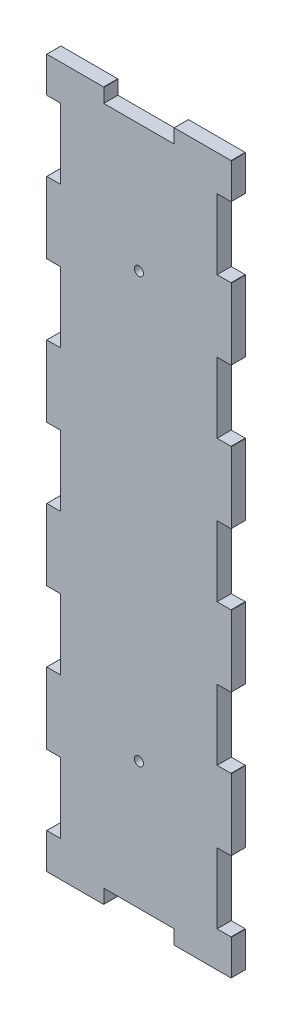
SolidWorks part; units mm, degrees
ref_plane "Front Plane" through (0, 0, 0) normal (0, 0, 1) x (1, 0, 0)
ref_plane "Top Plane" through (0, 0, 0) normal (0, 1, 0) x (1, 0, 0)
ref_plane "Right Plane" through (0, 0, 0) normal (1, 0, 0) x (0, 0, -1)
sketch "Model" plane through (0, 0, 0) normal (0, 0, 1) x (1, 0, 0)
  line L0 (-12.44, -124.95) -> (-12.43, -124.94)
  line L1 (-12.43, -124.94) -> (-12.42, -124.92)
  line L2 (-12.42, -124.92) -> (-12.41, -124.91)
  line L3 (-12.41, -124.91) -> (-12.4, -124.89)
  line L4 (-12.4, -124.89) -> (-12.4, -119.97)
  line L5 (-12.4, -119.97) -> (12.4, -119.97)
  line L6 (12.4, -119.97) -> (12.4, -124.89)
  line L7 (12.4, -124.89) -> (12.42, -124.93)
  line L8 (12.42, -124.93) -> (12.43, -124.94)
  line L9 (12.43, -124.94) -> (12.45, -124.95)
  line L10 (12.45, -124.95) -> (12.46, -124.96)
  line L11 (12.46, -124.96) -> (12.48, -124.97)
  line L12 (12.48, -124.97) -> (32.52, -124.97)
  line L13 (32.52, -124.97) -> (32.56, -124.95)
  line L14 (32.56, -124.95) -> (32.57, -124.94)
  line L15 (32.57, -124.94) -> (32.58, -124.92)
  line L16 (32.58, -124.92) -> (32.59, -124.91)
  line L17 (32.59, -124.91) -> (32.6, -124.89)
  line L18 (32.6, -124.89) -> (32.6, -112.48)
  line L19 (32.6, -112.48) -> (32.58, -112.44)
  line L20 (32.58, -112.44) -> (32.57, -112.43)
  line L21 (32.57, -112.43) -> (32.55, -112.42)
  line L22 (32.55, -112.42) -> (32.54, -112.41)
  line L23 (32.54, -112.41) -> (32.52, -112.4)
  line L24 (32.52, -112.4) -> (27.6, -112.4)
  line L25 (27.6, -112.4) -> (27.6, -87.6)
  line L26 (27.6, -87.6) -> (32.52, -87.6)
  line L27 (32.52, -87.6) -> (32.56, -87.58)
  line L28 (32.56, -87.58) -> (32.57, -87.57)
  line L29 (32.57, -87.57) -> (32.58, -87.55)
  line L30 (32.58, -87.55) -> (32.59, -87.54)
  line L31 (32.59, -87.54) -> (32.6, -87.52)
  line L32 (32.6, -87.52) -> (32.6, -62.48)
  line L33 (32.6, -62.48) -> (32.58, -62.44)
  line L34 (32.58, -62.44) -> (32.57, -62.43)
  line L35 (32.57, -62.43) -> (32.55, -62.42)
  line L36 (32.55, -62.42) -> (32.54, -62.41)
  line L37 (32.54, -62.41) -> (32.52, -62.4)
  line L38 (32.52, -62.4) -> (27.6, -62.4)
  line L39 (27.6, -62.4) -> (27.6, -37.6)
  line L40 (27.6, -37.6) -> (32.52, -37.6)
  line L41 (32.52, -37.6) -> (32.56, -37.58)
  line L42 (32.56, -37.58) -> (32.57, -37.57)
  line L43 (32.57, -37.57) -> (32.58, -37.55)
  line L44 (32.58, -37.55) -> (32.59, -37.54)
  line L45 (32.59, -37.54) -> (32.6, -37.52)
  line L46 (32.6, -37.52) -> (32.6, -12.48)
  line L47 (32.6, -12.48) -> (32.58, -12.44)
  line L48 (32.58, -12.44) -> (32.57, -12.43)
  line L49 (32.57, -12.43) -> (32.55, -12.42)
  line L50 (32.55, -12.42) -> (32.54, -12.41)
  line L51 (32.54, -12.41) -> (32.52, -12.4)
  line L52 (32.52, -12.4) -> (27.6, -12.4)
  line L53 (27.6, -12.4) -> (27.6, 12.4)
  line L54 (27.6, 12.4) -> (32.52, 12.4)
  line L55 (32.52, 12.4) -> (32.56, 12.42)
  line L56 (32.56, 12.42) -> (32.57, 12.43)
  line L57 (32.57, 12.43) -> (32.58, 12.45)
  line L58 (32.58, 12.45) -> (32.59, 12.46)
  line L59 (32.59, 12.46) -> (32.6, 12.48)
  line L60 (32.6, 12.48) -> (32.6, 37.52)
  line L61 (32.6, 37.52) -> (32.58, 37.56)
  line L62 (32.58, 37.56) -> (32.57, 37.57)
  line L63 (32.57, 37.57) -> (32.55, 37.58)
  line L64 (32.55, 37.58) -> (32.54, 37.59)
  line L65 (32.54, 37.59) -> (32.52, 37.6)
  line L66 (32.52, 37.6) -> (27.6, 37.6)
  line L67 (27.6, 37.6) -> (27.6, 62.4)
  line L68 (27.6, 62.4) -> (32.52, 62.4)
  line L69 (32.52, 62.4) -> (32.56, 62.42)
  line L70 (32.56, 62.42) -> (32.57, 62.43)
  line L71 (32.57, 62.43) -> (32.58, 62.45)
  line L72 (32.58, 62.45) -> (32.59, 62.46)
  line L73 (32.59, 62.46) -> (32.6, 62.48)
  line L74 (32.6, 62.48) -> (32.6, 87.52)
  line L75 (32.6, 87.52) -> (32.58, 87.56)
  line L76 (32.58, 87.56) -> (32.57, 87.57)
  line L77 (32.57, 87.57) -> (32.55, 87.58)
  line L78 (32.55, 87.58) -> (32.54, 87.59)
  line L79 (32.54, 87.59) -> (32.52, 87.6)
  line L80 (32.52, 87.6) -> (27.6, 87.6)
  line L81 (27.6, 87.6) -> (27.6, 112.4)
  line L82 (27.6, 112.4) -> (32.52, 112.4)
  line L83 (32.52, 112.4) -> (32.56, 112.42)
  line L84 (32.56, 112.42) -> (32.57, 112.43)
  line L85 (32.57, 112.43) -> (32.58, 112.45)
  line L86 (32.58, 112.45) -> (32.59, 112.46)
  line L87 (32.59, 112.46) -> (32.6, 112.48)
  line L88 (32.6, 112.48) -> (32.6, 124.89)
  line L89 (32.6, 124.89) -> (32.58, 124.93)
  line L90 (32.58, 124.93) -> (32.57, 124.94)
  line L91 (32.57, 124.94) -> (32.55, 124.95)
  line L92 (32.55, 124.95) -> (32.54, 124.96)
  line L93 (32.54, 124.96) -> (32.52, 124.97)
  line L94 (32.52, 124.97) -> (12.48, 124.97)
  line L95 (12.48, 124.97) -> (12.44, 124.95)
  line L96 (12.44, 124.95) -> (12.43, 124.94)
  line L97 (12.43, 124.94) -> (12.42, 124.92)
  line L98 (12.42, 124.92) -> (12.41, 124.91)
  line L99 (12.41, 124.91) -> (12.4, 124.89)
  line L100 (12.4, 124.89) -> (12.4, 119.97)
  line L101 (12.4, 119.97) -> (-12.4, 119.97)
  line L102 (-12.4, 119.97) -> (-12.4, 124.89)
  line L103 (-12.4, 124.89) -> (-12.42, 124.93)
  line L104 (-12.42, 124.93) -> (-12.43, 124.94)
  line L105 (-12.43, 124.94) -> (-12.45, 124.95)
  line L106 (-12.45, 124.95) -> (-12.46, 124.96)
  line L107 (-12.46, 124.96) -> (-12.48, 124.97)
  line L108 (-12.48, 124.97) -> (-32.52, 124.97)
  line L109 (-32.52, 124.97) -> (-32.56, 124.95)
  line L110 (-32.56, 124.95) -> (-32.57, 124.94)
  line L111 (-32.57, 124.94) -> (-32.58, 124.92)
  line L112 (-32.58, 124.92) -> (-32.59, 124.91)
  line L113 (-32.59, 124.91) -> (-32.6, 124.89)
  line L114 (-32.6, 124.89) -> (-32.6, 112.48)
  line L115 (-32.6, 112.48) -> (-32.58, 112.44)
  line L116 (-32.58, 112.44) -> (-32.57, 112.43)
  line L117 (-32.57, 112.43) -> (-32.55, 112.42)
  line L118 (-32.55, 112.42) -> (-32.54, 112.41)
  line L119 (-32.54, 112.41) -> (-32.52, 112.4)
  line L120 (-32.52, 112.4) -> (-27.6, 112.4)
  line L121 (-27.6, 112.4) -> (-27.6, 87.6)
  line L122 (-27.6, 87.6) -> (-32.52, 87.6)
  line L123 (-32.52, 87.6) -> (-32.56, 87.58)
  line L124 (-32.56, 87.58) -> (-32.57, 87.57)
  line L125 (-32.57, 87.57) -> (-32.58, 87.55)
  line L126 (-32.58, 87.55) -> (-32.59, 87.54)
  line L127 (-32.59, 87.54) -> (-32.6, 87.52)
  line L128 (-32.6, 87.52) -> (-32.6, 62.48)
  line L129 (-32.6, 62.48) -> (-32.58, 62.44)
  line L130 (-32.58, 62.44) -> (-32.57, 62.43)
  line L131 (-32.57, 62.43) -> (-32.55, 62.42)
  line L132 (-32.55, 62.42) -> (-32.54, 62.41)
  line L133 (-32.54, 62.41) -> (-32.52, 62.4)
  line L134 (-32.52, 62.4) -> (-27.6, 62.4)
  line L135 (-27.6, 62.4) -> (-27.6, 37.6)
  line L136 (-27.6, 37.6) -> (-32.52, 37.6)
  line L137 (-32.52, 37.6) -> (-32.56, 37.58)
  line L138 (-32.56, 37.58) -> (-32.57, 37.57)
  line L139 (-32.57, 37.57) -> (-32.58, 37.55)
  line L140 (-32.58, 37.55) -> (-32.59, 37.54)
  line L141 (-32.59, 37.54) -> (-32.6, 37.52)
  line L142 (-32.6, 37.52) -> (-32.6, 12.48)
  line L143 (-32.6, 12.48) -> (-32.58, 12.44)
  line L144 (-32.58, 12.44) -> (-32.57, 12.43)
  line L145 (-32.57, 12.43) -> (-32.55, 12.42)
  line L146 (-32.55, 12.42) -> (-32.54, 12.41)
  line L147 (-32.54, 12.41) -> (-32.52, 12.4)
  line L148 (-32.52, 12.4) -> (-27.6, 12.4)
  line L149 (-27.6, 12.4) -> (-27.6, -12.4)
  line L150 (-27.6, -12.4) -> (-32.52, -12.4)
  line L151 (-32.52, -12.4) -> (-32.56, -12.42)
  line L152 (-32.56, -12.42) -> (-32.57, -12.43)
  line L153 (-32.57, -12.43) -> (-32.58, -12.45)
  line L154 (-32.58, -12.45) -> (-32.59, -12.46)
  line L155 (-32.59, -12.46) -> (-32.6, -12.48)
  line L156 (-32.6, -12.48) -> (-32.6, -37.52)
  line L157 (-32.6, -37.52) -> (-32.58, -37.56)
  line L158 (-32.58, -37.56) -> (-32.57, -37.57)
  line L159 (-32.57, -37.57) -> (-32.55, -37.58)
  line L160 (-32.55, -37.58) -> (-32.54, -37.59)
  line L161 (-32.54, -37.59) -> (-32.52, -37.6)
  line L162 (-32.52, -37.6) -> (-27.6, -37.6)
  line L163 (-27.6, -37.6) -> (-27.6, -62.4)
  line L164 (-27.6, -62.4) -> (-32.52, -62.4)
  line L165 (-32.52, -62.4) -> (-32.56, -62.42)
  line L166 (-32.56, -62.42) -> (-32.57, -62.43)
  line L167 (-32.57, -62.43) -> (-32.58, -62.45)
  line L168 (-32.58, -62.45) -> (-32.59, -62.46)
  line L169 (-32.59, -62.46) -> (-32.6, -62.48)
  line L170 (-32.6, -62.48) -> (-32.6, -87.52)
  line L171 (-32.6, -87.52) -> (-32.58, -87.56)
  line L172 (-32.58, -87.56) -> (-32.57, -87.57)
  line L173 (-32.57, -87.57) -> (-32.55, -87.58)
  line L174 (-32.55, -87.58) -> (-32.54, -87.59)
  line L175 (-32.54, -87.59) -> (-32.52, -87.6)
  line L176 (-32.52, -87.6) -> (-27.6, -87.6)
  line L177 (-27.6, -87.6) -> (-27.6, -112.4)
  line L178 (-27.6, -112.4) -> (-32.52, -112.4)
  line L179 (-32.52, -112.4) -> (-32.56, -112.42)
  line L180 (-32.56, -112.42) -> (-32.57, -112.43)
  line L181 (-32.57, -112.43) -> (-32.58, -112.45)
  line L182 (-32.58, -112.45) -> (-32.59, -112.46)
  line L183 (-32.59, -112.46) -> (-32.6, -112.48)
  line L184 (-32.6, -112.48) -> (-32.6, -124.89)
  line L185 (-32.6, -124.89) -> (-32.58, -124.93)
  line L186 (-32.58, -124.93) -> (-32.57, -124.94)
  line L187 (-32.57, -124.94) -> (-32.55, -124.95)
  line L188 (-32.55, -124.95) -> (-32.54, -124.96)
  line L189 (-32.54, -124.96) -> (-32.52, -124.97)
  line L190 (-32.52, -124.97) -> (-12.48, -124.97)
  line L191 (-12.48, -124.97) -> (-12.44, -124.95)
extrude "Boss-Extrude1" add sketch "Model" along normal blind 5
sketch "Sketch1" plane through (0, 0, 5) normal (0, 0, 1) x (1, 0, 0)
  line L1 (-27.6, 119.97) -> (27.6, 119.97) construction
  line L2 (-27.6, 119.97) -> (-27.6, -119.97) construction
  line L3 (-27.6, -119.97) -> (27.6, -119.97) construction
  line L4 (27.6, 119.97) -> (27.6, -119.97) construction
  line L5 (-27.6, 119.97) -> (27.6, -119.97) construction
  line L6 (-27.6, -119.97) -> (27.6, 119.97) construction
  line L8 (-27.6, 0) -> (27.6, 0) construction
  line L9 (-12.4, -119.97) -> (12.4, -119.97) construction
  line L10 (27.6, -112.4) -> (27.6, -87.6) construction
  circle A0 centre (0, 74.935) radius 1.6
  circle A1 centre (0, -74.935) radius 1.6
  point P4 (0, 0)
  point P6 (0, 0)
  point P7 (0, 0)
  dimension "D1" = 3.2
  dimension "D2" = 149.87
extrude "Cut-Extrude1" cut sketch "Sketch1" against normal through all
